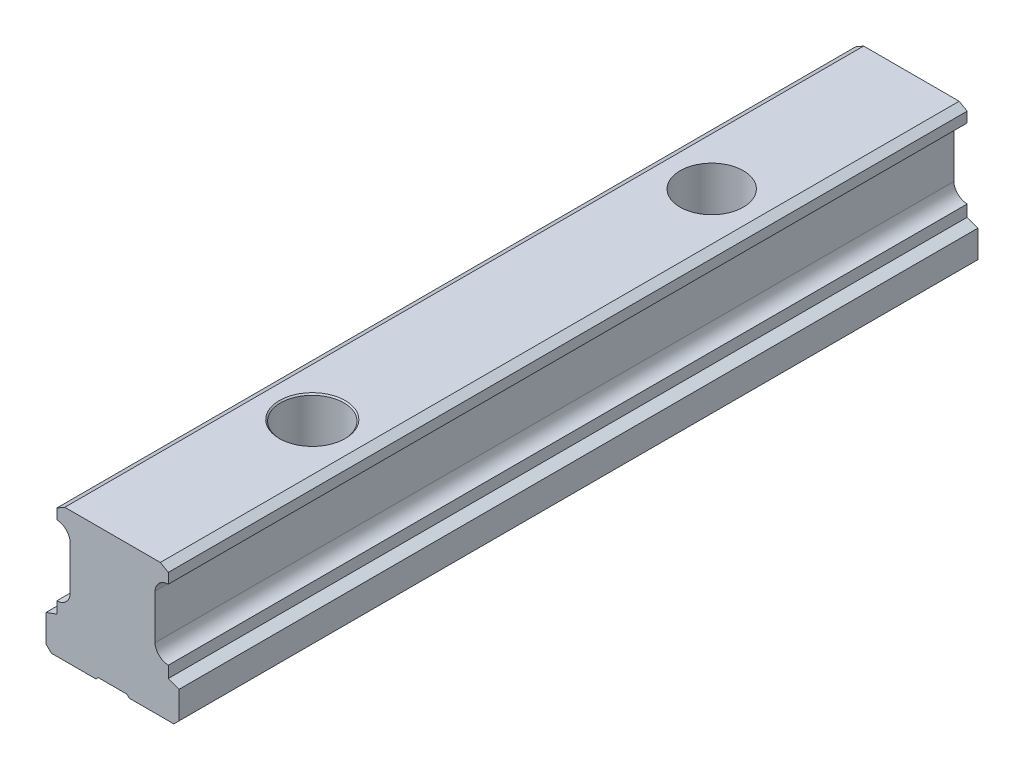
SolidWorks part; units mm, degrees
ref_plane "Plan de face" through (0, 0, 0) normal (0, 0, 1) x (1, 0, 0)
ref_plane "Plan de dessus" through (0, 0, 0) normal (0, 1, 0) x (1, 0, 0)
ref_plane "Plan de droite" through (0, 0, 0) normal (1, 0, 0) x (0, 0, -1)
ref_plane "Plan1" through (0, 0, 0) normal (0, 0, -1) x (-1, 0, 0)
sketch "Esquisse1" plane through (0, 0, 0) normal (0, 0, -1) x (-1, 0, 0)
  line L0 (-19.2, 7.9737) -> (-19.2, 0)
  line L1 (-19.2, 0) -> (0.8, 0)
  line L2 (0.8, 0) -> (0.8, 20)
  line L3 (0.8, 20) -> (-17.575, 20)
  line L4 (-17.575, 20) -> (-17.575, 17.7671)
  line L5 (-15.5625, 15.8524) -> (-15.5625, 9.1476)
  arc A0 (-15.5625, 9.1476) -> (-19.2, 7.9737) centre (-17.6174, 9.2924) cw
  arc A1 (-17.575, 17.7671) -> (-15.5625, 15.8524) centre (-17.6174, 15.7076) cw
extrude "Boss.-Extru.1" add sketch "Esquisse1" against normal blind 1980
sketch "Esquisse2" plane through (0, 0, 1980) normal (0, 0, 1) x (1, 0, 0)
  line L0 (17.575, 7.2329) -> (17.575, 4.9085)
  line L1 (17.575, 4.9085) -> (19.2, 4.9085)
  line L2 (19.2, 4.9085) -> (19.2, 7.9737)
  arc A0 (19.2, 7.9737) -> (17.575, 7.2329) centre (17.6174, 9.2924) cw
extrude "Enlèv. mat.-Extru.1" cut sketch "Esquisse2" against normal through all
sketch "Esquisse3" plane through (0, 0, 1980) normal (0, 0, 1) x (1, 0, 0)
  line L0 (7.05, 0) -> (11.35, 0)
  line L1 (11.35, 0) -> (11.35, 0.35)
  line L2 (11.35, 0.35) -> (7.05, 0.35)
  line L3 (7.05, 0.35) -> (7.05, 0)
extrude "Enlèv. mat.-Extru.2" cut sketch "Esquisse3" against normal blind 1980
sketch "Esquisse4" plane through (0, 0, 1980) normal (0, 0, 1) x (1, 0, 0)
  line L0 (-0.8, 5.5) -> (0.825, 5.5)
  line L1 (0.825, 5.5) -> (0.825, 20)
  line L2 (0.825, 20) -> (-0.8, 20)
  line L3 (-0.8, 20) -> (-0.8, 5.5)
extrude "Enlèv. mat.-Extru.3" cut sketch "Esquisse4" against normal through all
sketch "Esquisse5" plane through (0, 0, 1980) normal (0, 0, 1) x (1, 0, 0)
  line L0 (0.825, 17.7671) -> (0.825, 7.2329)
  line L1 (2.8375, 9.1476) -> (2.8375, 15.8524)
  arc A0 (0.825, 7.2329) -> (2.8375, 9.1476) centre (0.7826, 9.2924) ccw
  arc A1 (2.8375, 15.8524) -> (0.825, 17.7671) centre (0.7826, 15.7076) ccw
extrude "Enlèv. mat.-Extru.4" cut sketch "Esquisse5" against normal through all
draft "Dépouille1" type of draft neutral plane draft angle 20 faces to draft 1 face at (0.0125, 5.5, 990) neutral plane through (0.825, 5.5, 0) neutral plane normal (-1, 0, 0) parameters "D1"=20
draft "Dépouille2" type of draft neutral plane draft angle 20 faces to draft 1 face at (18.3875, 4.9085, 990) neutral plane through (19.2, 7.9737, 1980) neutral plane normal (1, 0, 0) parameters "D1"=20
draft "Dépouille3" type of draft neutral plane draft angle 45 faces to draft 2 face at (11.35, 0.175, 990) face at (7.05, 0.175, 990) neutral plane through (11.35, 0.35, 0) neutral plane normal (0, -1, 0) parameters "D1"=45
hole_wizard "Perçage1" positions "Esquisse7" profile "Esquisse6" legacy
sketch "Esquisse7" plane through (0, 20, 0) normal (0, 1, 0) x (1, 0, 0)
  point P0 (9.2, -30)
  point P1 (9.2, -90)
  point P2 (9.2, -150)
  point P3 (9.2, -210)
  point P4 (9.2, -270)
  point P5 (9.2, -330)
  point P6 (9.2, -390)
  point P7 (9.2, -450)
  point P8 (9.2, -510)
  point P9 (9.2, -570)
  point P10 (9.2, -630)
  point P11 (9.2, -690)
  point P12 (9.2, -750)
  point P13 (9.2, -810)
  point P14 (9.2, -870)
  point P15 (9.2, -930)
  point P16 (9.2, -990)
  point P17 (9.2, -1050)
  point P18 (9.2, -1110)
  point P19 (9.2, -1170)
  point P20 (9.2, -1230)
  point P21 (9.2, -1290)
  point P22 (9.2, -1350)
  point P23 (9.2, -1410)
  point P24 (9.2, -1470)
  point P25 (9.2, -1530)
  point P26 (9.2, -1590)
  point P27 (9.2, -1650)
  point P28 (9.2, -1710)
  point P29 (9.2, -1770)
  point P30 (9.2, -1830)
  point P31 (9.2, -1890)
  point P32 (9.2, -1950)
sketch "Esquisse6" plane through (9.2, 20, 30) normal (1, 0, 0) x (0, 0, 1)
  line L0 (0, 0) -> (0, 20)
  line L1 (0, 20) -> (3, 20)
  line L2 (3, 20) -> (3, 8.5)
  line L3 (3, 8.5) -> (4.75, 8.5)
  line L4 (4.75, 8.5) -> (4.75, 0)
  line L5 (4.75, 0) -> (0, 0)
  line L6 (0, 110) -> (0, -10) construction
  dimension "Diamètre" = 6
  dimension "Profondeur" = 20
  dimension "Diamètre chambrage" = 9.5
  dimension "Profondeur chambrage" = 8.5
chamfer "Chanfrein1" distance 0.8 angle 45 2 edges at (19.2, 0, 990) (-0.8, 0, 990)
chamfer "Chanfrein2" distance 1.2 angle 30 1 edges at (0.825, 20, 990)
chamfer "Chanfrein3" distance 0.2 angle 45 3 edges at (12.2, 0, 1950) (6.2, 0, 1950) (9.2, 20, 1954.75)
chamfer "Chanfrein4" distance 0.6928 angle 60 1 edges at (17.575, 20, 990)
ref_plane "Plan2" through (0, 0, 1980) normal (0, 0, 1) x (1, 0, 0)
sketch "Esquisse12" plane through (0, 0, 1980) normal (0, 0, 1) x (1, 0, 0)
  line L0 (-23.2139, 45.9286) -> (54.94, 45.9286)
  line L1 (-23.2139, 45.9286) -> (-23.2139, -28.586)
  line L2 (-23.2139, -28.586) -> (54.94, -28.586)
  line L3 (54.94, 45.9286) -> (54.94, -28.586)
extrude "Enlèv. mat.-Extru.5" cut sketch "Esquisse12" against normal through all from offset 120
